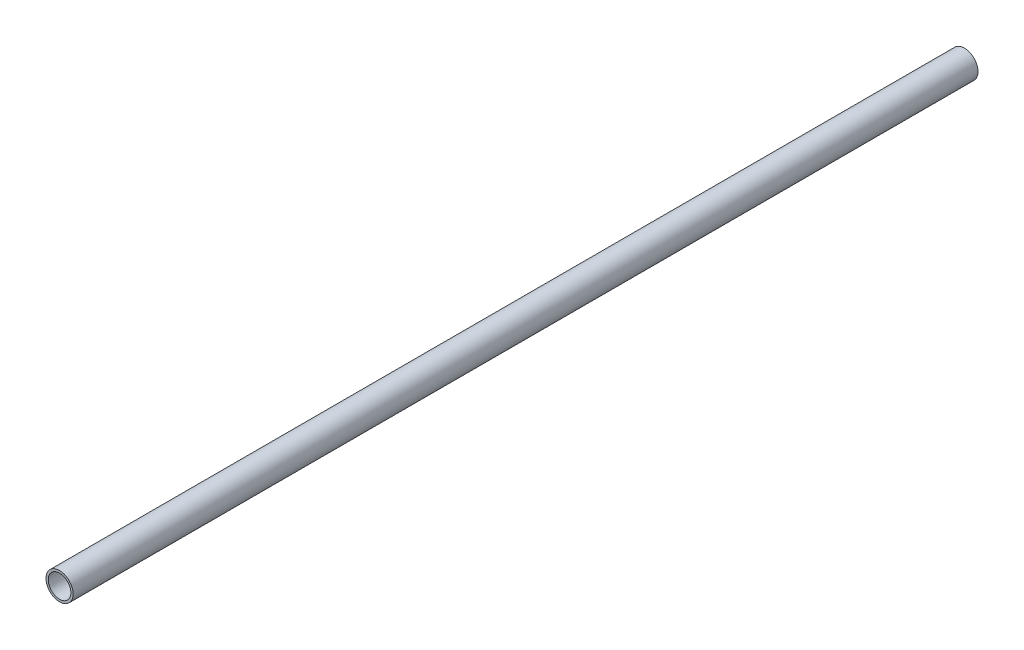
SolidWorks part; units mm, degrees
material "AISI 316 Stainless Steel Sheet (SS)"
ref_plane "Front Plane" through (0, 0, 0) normal (0, 0, 1) x (1, 0, 0)
ref_plane "Top Plane" through (0, 0, 0) normal (0, 1, 0) x (1, 0, 0)
ref_plane "Right Plane" through (0, 0, 0) normal (1, 0, 0) x (0, 0, -1)
sketch "Sketch1" plane through (0, 0, 0) normal (0, 0, 1) x (1, 0, 0)
  circle A0 centre (0, 0) radius 6
  circle A1 centre (0, 0) radius 5
  dimension "D1" = 12
  dimension "D2" = 10
extrude "Boss-Extrude1" add sketch "Sketch1" along normal blind 400
